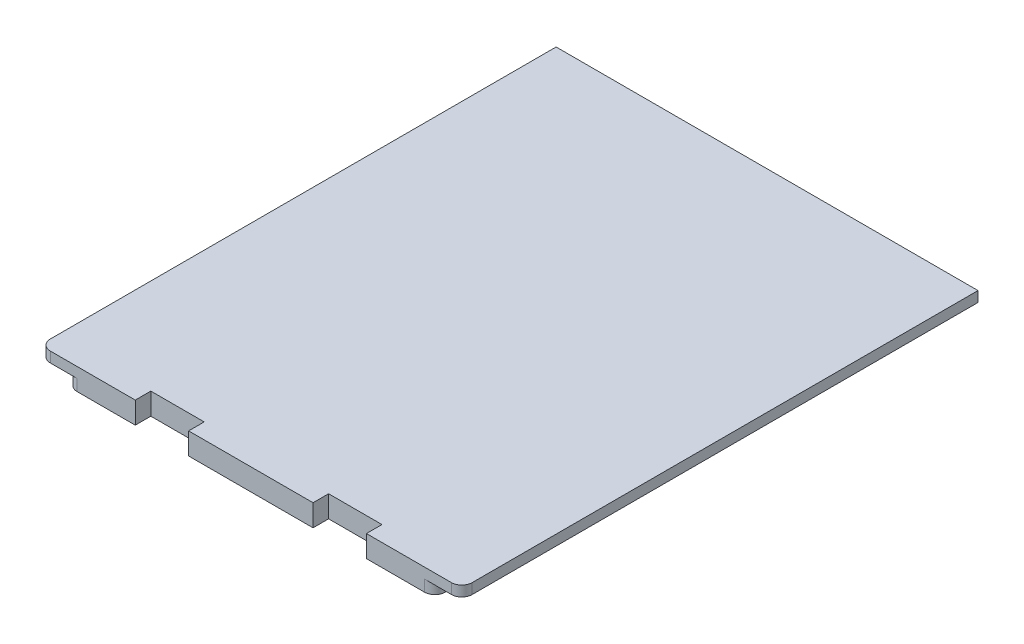
SolidWorks part; units mm, degrees
ref_plane "Front Plane" through (0, 0, 0) normal (0, 0, 1) x (1, 0, 0)
ref_plane "Top Plane" through (0, 0, 0) normal (0, 1, 0) x (1, 0, 0)
ref_plane "Right Plane" through (0, 0, 0) normal (1, 0, 0) x (0, 0, -1)
sketch "Sketch2" plane through (0, 0, 0) normal (0, 0, 1) x (1, 0, 0)
  line L0 (35.5, 0) -> (-35.5, 0)
  line L1 (-35.5, 0) -> (-35.5, 2.2)
  line L2 (-35.5, 2.2) -> (-40.7, 2.2)
  line L3 (-40.7, 2.2) -> (-40.7, 4.2)
  line L4 (-40.7, 4.2) -> (40.7, 4.2)
  line L5 (40.7, 4.2) -> (40.7, 2.2)
  line L6 (40.7, 2.2) -> (35.5, 2.2)
  line L7 (35.5, 2.2) -> (35.5, 0)
  point P0 (0, 4.2)
  point P4 (0, 0)
  dimension "D1" = 2
  dimension "D2" = 81.4
  dimension "D3" = 5.2
  dimension "D4" = 2.2
extrude "Boss-Extrude1" add sketch "Sketch2" along normal blind 99.6
fillet "Fillet1" radius 2 2 edges at (-40.7, 3.2, 99.6) (40.7, 3.2, 99.6)
sketch "Sketch3" plane through (0, 0, 0) normal (0, -1, 0) x (-1, 0, 0)
  line L0 (35.5, -99.6) -> (-35.5, -99.6) construction
  line L1 (-22.3, -96.6) -> (-12.0022, -96.6)
  line L2 (-22.3, -96.6) -> (-22.3, -99.6)
  line L3 (-22.3, -99.6) -> (-12.0022, -99.6)
  line L4 (22.3, -96.6) -> (22.3, -99.6)
  line L5 (-22.3, -96.6) -> (22.3, -99.6) construction
  line L6 (-22.3, -99.6) -> (22.3, -96.6) construction
  line L7 (12.0022, -96.6) -> (22.3, -96.6)
  line L9 (-12.0022, -99.6) -> (-12.0022, -96.6)
  line L11 (12.0022, -99.6) -> (12.0022, -96.6)
  line L12 (12.0022, -99.6) -> (22.3, -99.6)
  point P0 (0, -98.1)
  point P9 (0, -97.5578)
  line M7 (-35.5, -99.6) -> (35.5, -99.6)
  dimension "D1" = 44.6
  dimension "D2" = 3
  dimension "D3" = 10.2978
extrude "Cut-Extrude1" cut sketch "Sketch3" against normal blind 5 contours L11 L4 L7 M7 | L9 L1 L2 M7
fillet "Fillet2" radius 2 2 edges at (35.5, 1.1, 99.6) (-35.5, 1.1, 99.6)
